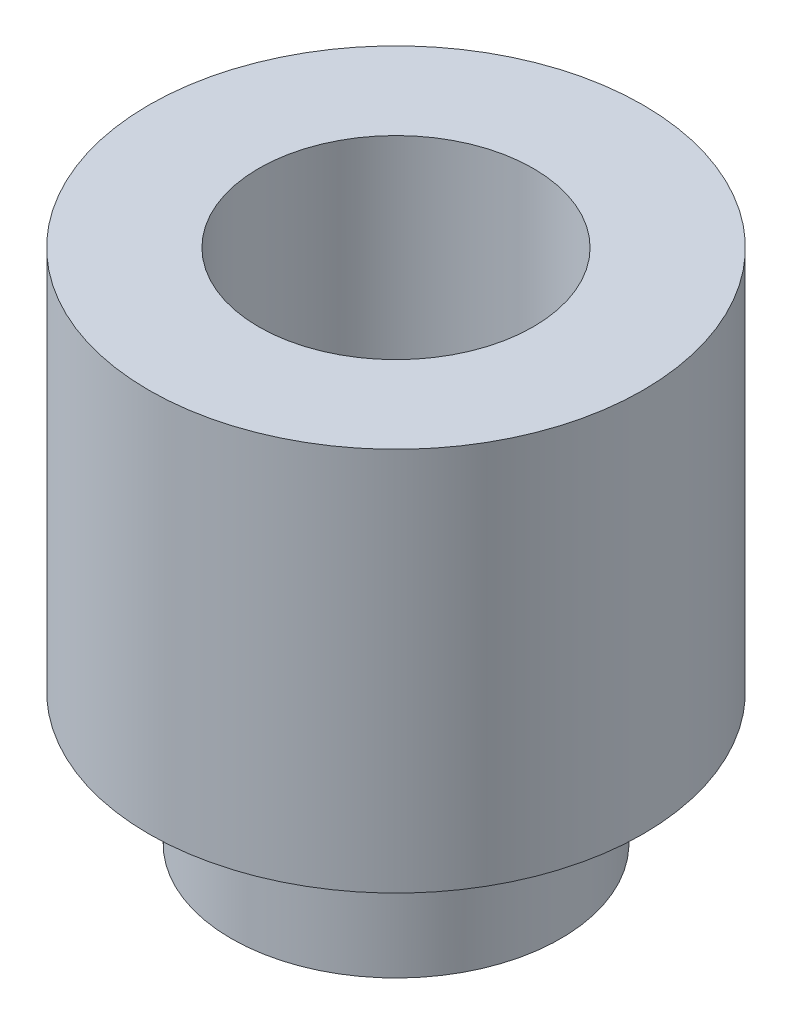
SolidWorks part; units mm, degrees
ref_plane "前视基准面" through (0, 0, 0) normal (0, 0, 1) x (1, 0, 0)
ref_plane "上视基准面" through (0, 0, 0) normal (0, 1, 0) x (1, 0, 0)
ref_plane "右视基准面" through (0, 0, 0) normal (1, 0, 0) x (0, 0, -1)
other "Configuration Table"
sketch "草图1" plane through (0, 0, 0) normal (0, 1, 0) x (1, 0, 0)
  circle A0 centre (0, 0) radius 2.25
  circle A1 centre (0, 0) radius 1.25
  dimension "D1" = 4.5
  dimension "D2" = 2.5
extrude "凸台-拉伸1" add sketch "草图1" along normal blind 3.5
sketch "草图2" plane through (0, 0, 0) normal (0, -1, 0) x (1, 0, 0)
  circle A0 centre (0, 0) radius 1.5
  circle A1 centre (0, 0) radius 1.25 construction
  circle A2 centre (0, 0) radius 1.25
  dimension "D1" = 3
extrude "凸台-拉伸2" add sketch "草图2" along normal blind 1.2
